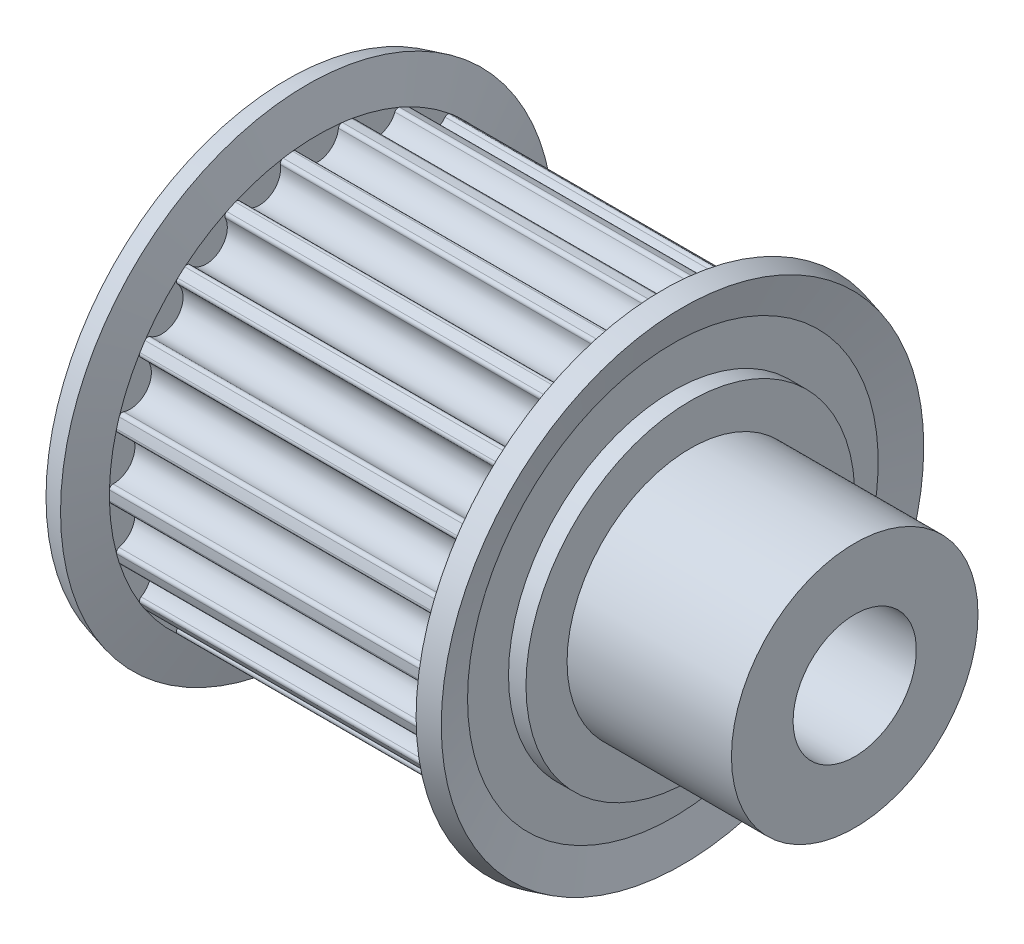
SolidWorks part; units mm, degrees
ref_plane "Front Plane" through (0, 0, 0) normal (0, 0, 1) x (1, 0, 0)
ref_plane "Top Plane" through (0, 0, 0) normal (0, 1, 0) x (1, 0, 0)
ref_plane "Right Plane" through (0, 0, 0) normal (1, 0, 0) x (0, 0, -1)
ref_plane "Plane1" through (0, 0, 0) normal (0, 0, 1) x (1, 0, 0)
sketch "Sketch1" plane through (0, 0, 0) normal (0, 0, 1) x (1, 0, 0)
  line L0 (0, 0) -> (0, 8)
  line L1 (0, 8) -> (0.85, 8)
  line L2 (0.85, 8) -> (0.85, 9.9933)
  line L3 (0.85, 9.9933) -> (0.3817, 11.7412)
  line L4 (0.3817, 11.7412) -> (1.3476, 12)
  line L5 (1.3476, 12) -> (1.85, 10.125)
  line L6 (1.85, 10.125) -> (18.15, 10.125)
  line L7 (18.15, 10.125) -> (18.6524, 12)
  line L8 (18.6524, 12) -> (19.6183, 11.7412)
  line L9 (19.6183, 11.7412) -> (19.15, 9.9933)
  line L10 (19.15, 9.9933) -> (19.15, 8)
  line L11 (19.15, 8) -> (20, 8)
  line L12 (20, 8) -> (20, 6)
  line L13 (20, 6) -> (28, 6)
  line L14 (28, 6) -> (28, 0)
  line L15 (28, 0) -> (0, 0)
  line L16 (28, 0) -> (0, 0) construction
revolve "Revolve1" add sketch "Sketch1" angle 360 about L16
ref_plane "Plane2" through (10, 0, 0) normal (1, 0, 0) x (0, 0, -1)
sketch "Sketch2" plane through (10, 0, 0) normal (1, 0, 0) x (0, 0, -1)
  line L0 (-1.2586, 10.4293) -> (-1.2131, 10.0521)
  line L1 (1.2131, 10.0521) -> (1.2586, 10.4293)
  arc A0 (-1.2131, 10.0521) -> (-1.0238, 9.9019) centre (-1.1927, 9.8833) cw
  arc A1 (-1.0238, 9.9019) -> (1.0238, 9.9019) centre (0, 10.015) ccw
  arc A2 (1.0238, 9.9019) -> (1.2131, 10.0521) centre (1.1927, 9.8833) cw
  arc A3 (1.2586, 10.4293) -> (-1.2586, 10.4293) centre (0, 0) ccw
extrude "Cut-Extrude1" cut sketch "Sketch2" against normal blind 8.15 and the other way blind 8.15
ref_plane "Plane3" through (10, 0, 0) normal (1, 0, 0) x (0, 0, -1)
sketch "Sketch3" plane through (10, 0, 0) normal (1, 0, 0) x (0, 0, -1)
  line L0 (-4.1459, 9.6523) -> (-3.996, 9.3031)
  line L1 (-1.668, 9.9867) -> (-1.7306, 10.3615)
  arc A0 (-3.996, 9.3031) -> (-3.772, 9.2124) centre (-3.9289, 9.1469) cw
  arc A1 (-3.772, 9.2124) -> (-1.8074, 9.7893) centre (-2.8216, 9.6093) ccw
  arc A2 (-1.8074, 9.7893) -> (-1.668, 9.9867) centre (-1.64, 9.819) cw
  arc A3 (-1.7306, 10.3615) -> (-4.1459, 9.6523) centre (0, 0) ccw
extrude "Cut-Extrude2" cut sketch "Sketch3" against normal blind 8.15 and the other way blind 8.15
ref_plane "Plane4" through (10, 0, 0) normal (1, 0, 0) x (0, 0, -1)
sketch "Sketch4" plane through (10, 0, 0) normal (1, 0, 0) x (0, 0, -1)
  line L0 (-6.6974, 8.0932) -> (-6.4551, 7.8005)
  line L1 (-4.414, 9.1122) -> (-4.5797, 9.4542)
  arc A0 (-6.4551, 7.8005) -> (-6.2147, 7.7766) centre (-6.3467, 7.6695) cw
  arc A1 (-6.2147, 7.7766) -> (-4.4921, 8.8835) centre (-5.4145, 8.4252) ccw
  arc A2 (-4.4921, 8.8835) -> (-4.414, 9.1122) centre (-4.3399, 8.9592) cw
  arc A3 (-4.5797, 9.4542) -> (-6.6974, 8.0932) centre (0, 0) ccw
extrude "Cut-Extrude3" cut sketch "Sketch4" against normal blind 8.15 and the other way blind 8.15
ref_plane "Plane5" through (10, 0, 0) normal (1, 0, 0) x (0, 0, -1)
sketch "Sketch5" plane through (10, 0, 0) normal (1, 0, 0) x (0, 0, -1)
  line L0 (-8.7062, 5.8785) -> (-8.3913, 5.6659)
  line L1 (-6.8024, 7.4995) -> (-7.0577, 7.781)
  arc A0 (-8.3913, 5.6659) -> (-8.1538, 5.7107) centre (-8.2504, 5.5708) cw
  arc A1 (-8.1538, 5.7107) -> (-6.813, 7.2581) centre (-7.5688, 6.5584) ccw
  arc A2 (-6.813, 7.2581) -> (-6.8024, 7.4995) centre (-6.6882, 7.3736) cw
  arc A3 (-7.0577, 7.781) -> (-8.7062, 5.8785) centre (0, 0) ccw
extrude "Cut-Extrude4" cut sketch "Sketch5" against normal blind 8.15 and the other way blind 8.15
ref_plane "Plane6" through (10, 0, 0) normal (1, 0, 0) x (0, 0, -1)
sketch "Sketch6" plane through (10, 0, 0) normal (1, 0, 0) x (0, 0, -1)
  line L0 (-10.0097, 3.1876) -> (-9.6476, 3.0723)
  line L1 (-8.6397, 5.2793) -> (-8.964, 5.4774)
  arc A0 (-9.6476, 3.0723) -> (-9.4324, 3.1822) centre (-9.4856, 3.0207) cw
  arc A1 (-9.4324, 3.1822) -> (-8.5818, 5.0447) centre (-9.11, 4.1604) ccw
  arc A2 (-8.5818, 5.0447) -> (-8.6397, 5.2793) centre (-8.4947, 5.1906) cw
  arc A3 (-8.964, 5.4774) -> (-10.0097, 3.1876) centre (0, 0) ccw
extrude "Cut-Extrude5" cut sketch "Sketch6" against normal blind 8.15 and the other way blind 8.15
ref_plane "Plane7" through (10, 0, 0) normal (1, 0, 0) x (0, 0, -1)
sketch "Sketch7" plane through (10, 0, 0) normal (1, 0, 0) x (0, 0, -1)
  line L0 (-10.5023, 0.2384) -> (-10.1224, 0.2298)
  line L1 (-9.7771, 2.6313) -> (-10.144, 2.7301)
  arc A0 (-10.1224, 0.2298) -> (-9.9469, 0.3958) centre (-9.9524, 0.2259) cw
  arc A1 (-9.9469, 0.3958) -> (-9.6555, 2.4226) centre (-9.9131, 1.4253) ccw
  arc A2 (-9.6555, 2.4226) -> (-9.7771, 2.6313) centre (-9.6129, 2.5871) cw
  arc A3 (-10.144, 2.7301) -> (-10.5023, 0.2384) centre (0, 0) ccw
extrude "Cut-Extrude6" cut sketch "Sketch7" against normal blind 8.15 and the other way blind 8.15
ref_plane "Plane8" through (10, 0, 0) normal (1, 0, 0) x (0, 0, -1)
sketch "Sketch8" plane through (10, 0, 0) normal (1, 0, 0) x (0, 0, -1)
  line L0 (-10.144, -2.7301) -> (-9.7771, -2.6313)
  line L1 (-10.1224, -0.2298) -> (-10.5023, -0.2384)
  arc A0 (-9.7771, -2.6313) -> (-9.6555, -2.4226) centre (-9.6129, -2.5871) cw
  arc A1 (-9.6555, -2.4226) -> (-9.9469, -0.3958) centre (-9.9131, -1.4253) ccw
  arc A2 (-9.9469, -0.3958) -> (-10.1224, -0.2298) centre (-9.9524, -0.2259) cw
  arc A3 (-10.5023, -0.2384) -> (-10.144, -2.7301) centre (0, 0) ccw
extrude "Cut-Extrude7" cut sketch "Sketch8" against normal blind 8.15 and the other way blind 8.15
ref_plane "Plane9" through (10, 0, 0) normal (1, 0, 0) x (0, 0, -1)
sketch "Sketch9" plane through (10, 0, 0) normal (1, 0, 0) x (0, 0, -1)
  line L0 (-8.964, -5.4774) -> (-8.6397, -5.2793)
  line L1 (-9.6476, -3.0723) -> (-10.0097, -3.1876)
  arc A0 (-8.6397, -5.2793) -> (-8.5818, -5.0447) centre (-8.4947, -5.1906) cw
  arc A1 (-8.5818, -5.0447) -> (-9.4324, -3.1822) centre (-9.11, -4.1604) ccw
  arc A2 (-9.4324, -3.1822) -> (-9.6476, -3.0723) centre (-9.4856, -3.0207) cw
  arc A3 (-10.0097, -3.1876) -> (-8.964, -5.4774) centre (0, 0) ccw
extrude "Cut-Extrude8" cut sketch "Sketch9" against normal blind 8.15 and the other way blind 8.15
ref_plane "Plane10" through (10, 0, 0) normal (1, 0, 0) x (0, 0, -1)
sketch "Sketch10" plane through (10, 0, 0) normal (1, 0, 0) x (0, 0, -1)
  line L0 (-7.0577, -7.781) -> (-6.8024, -7.4995)
  line L1 (-8.3913, -5.6659) -> (-8.7062, -5.8785)
  arc A0 (-6.8024, -7.4995) -> (-6.813, -7.2581) centre (-6.6882, -7.3736) cw
  arc A1 (-6.813, -7.2581) -> (-8.1538, -5.7107) centre (-7.5688, -6.5584) ccw
  arc A2 (-8.1538, -5.7107) -> (-8.3913, -5.6659) centre (-8.2504, -5.5708) cw
  arc A3 (-8.7062, -5.8785) -> (-7.0577, -7.781) centre (0, 0) ccw
extrude "Cut-Extrude9" cut sketch "Sketch10" against normal blind 8.15 and the other way blind 8.15
ref_plane "Plane11" through (10, 0, 0) normal (1, 0, 0) x (0, 0, -1)
sketch "Sketch11" plane through (10, 0, 0) normal (1, 0, 0) x (0, 0, -1)
  line L0 (-4.5797, -9.4542) -> (-4.414, -9.1122)
  line L1 (-6.4551, -7.8005) -> (-6.6974, -8.0932)
  arc A0 (-4.414, -9.1122) -> (-4.4921, -8.8835) centre (-4.3399, -8.9592) cw
  arc A1 (-4.4921, -8.8835) -> (-6.2147, -7.7766) centre (-5.4145, -8.4252) ccw
  arc A2 (-6.2147, -7.7766) -> (-6.4551, -7.8005) centre (-6.3467, -7.6695) cw
  arc A3 (-6.6974, -8.0932) -> (-4.5797, -9.4542) centre (0, 0) ccw
extrude "Cut-Extrude10" cut sketch "Sketch11" against normal blind 8.15 and the other way blind 8.15
ref_plane "Plane12" through (10, 0, 0) normal (1, 0, 0) x (0, 0, -1)
sketch "Sketch12" plane through (10, 0, 0) normal (1, 0, 0) x (0, 0, -1)
  line L0 (-1.7306, -10.3615) -> (-1.668, -9.9867)
  line L1 (-3.996, -9.3031) -> (-4.1459, -9.6523)
  arc A0 (-1.668, -9.9867) -> (-1.8074, -9.7893) centre (-1.64, -9.819) cw
  arc A1 (-1.8074, -9.7893) -> (-3.772, -9.2124) centre (-2.8216, -9.6093) ccw
  arc A2 (-3.772, -9.2124) -> (-3.996, -9.3031) centre (-3.9289, -9.1469) cw
  arc A3 (-4.1459, -9.6523) -> (-1.7306, -10.3615) centre (0, 0) ccw
extrude "Cut-Extrude11" cut sketch "Sketch12" against normal blind 8.15 and the other way blind 8.15
ref_plane "Plane13" through (10, 0, 0) normal (1, 0, 0) x (0, 0, -1)
sketch "Sketch13" plane through (10, 0, 0) normal (1, 0, 0) x (0, 0, -1)
  line L0 (1.2586, -10.4293) -> (1.2131, -10.0521)
  line L1 (-1.2131, -10.0521) -> (-1.2586, -10.4293)
  arc A0 (1.2131, -10.0521) -> (1.0238, -9.9019) centre (1.1927, -9.8833) cw
  arc A1 (1.0238, -9.9019) -> (-1.0238, -9.9019) centre (0, -10.015) ccw
  arc A2 (-1.0238, -9.9019) -> (-1.2131, -10.0521) centre (-1.1927, -9.8833) cw
  arc A3 (-1.2586, -10.4293) -> (1.2586, -10.4293) centre (0, 0) ccw
extrude "Cut-Extrude12" cut sketch "Sketch13" against normal blind 8.15 and the other way blind 8.15
ref_plane "Plane14" through (10, 0, 0) normal (1, 0, 0) x (0, 0, -1)
sketch "Sketch14" plane through (10, 0, 0) normal (1, 0, 0) x (0, 0, -1)
  line L0 (4.1459, -9.6523) -> (3.996, -9.3031)
  line L1 (1.668, -9.9867) -> (1.7306, -10.3615)
  arc A0 (3.996, -9.3031) -> (3.772, -9.2124) centre (3.9289, -9.1469) cw
  arc A1 (3.772, -9.2124) -> (1.8074, -9.7893) centre (2.8216, -9.6093) ccw
  arc A2 (1.8074, -9.7893) -> (1.668, -9.9867) centre (1.64, -9.819) cw
  arc A3 (1.7306, -10.3615) -> (4.1459, -9.6523) centre (0, 0) ccw
extrude "Cut-Extrude13" cut sketch "Sketch14" against normal blind 8.15 and the other way blind 8.15
ref_plane "Plane15" through (10, 0, 0) normal (1, 0, 0) x (0, 0, -1)
sketch "Sketch15" plane through (10, 0, 0) normal (1, 0, 0) x (0, 0, -1)
  line L0 (6.6974, -8.0932) -> (6.4551, -7.8005)
  line L1 (4.414, -9.1122) -> (4.5797, -9.4542)
  arc A0 (6.4551, -7.8005) -> (6.2147, -7.7766) centre (6.3467, -7.6695) cw
  arc A1 (6.2147, -7.7766) -> (4.4921, -8.8835) centre (5.4145, -8.4252) ccw
  arc A2 (4.4921, -8.8835) -> (4.414, -9.1122) centre (4.3399, -8.9592) cw
  arc A3 (4.5797, -9.4542) -> (6.6974, -8.0932) centre (0, 0) ccw
extrude "Cut-Extrude14" cut sketch "Sketch15" against normal blind 8.15 and the other way blind 8.15
ref_plane "Plane16" through (10, 0, 0) normal (1, 0, 0) x (0, 0, -1)
sketch "Sketch16" plane through (10, 0, 0) normal (1, 0, 0) x (0, 0, -1)
  line L0 (8.7062, -5.8785) -> (8.3913, -5.6659)
  line L1 (6.8024, -7.4995) -> (7.0577, -7.781)
  arc A0 (8.3913, -5.6659) -> (8.1538, -5.7107) centre (8.2504, -5.5708) cw
  arc A1 (8.1538, -5.7107) -> (6.813, -7.2581) centre (7.5688, -6.5584) ccw
  arc A2 (6.813, -7.2581) -> (6.8024, -7.4995) centre (6.6882, -7.3736) cw
  arc A3 (7.0577, -7.781) -> (8.7062, -5.8785) centre (0, 0) ccw
extrude "Cut-Extrude15" cut sketch "Sketch16" against normal blind 8.15 and the other way blind 8.15
ref_plane "Plane17" through (10, 0, 0) normal (1, 0, 0) x (0, 0, -1)
sketch "Sketch17" plane through (10, 0, 0) normal (1, 0, 0) x (0, 0, -1)
  line L0 (10.0097, -3.1876) -> (9.6476, -3.0723)
  line L1 (8.6397, -5.2793) -> (8.964, -5.4774)
  arc A0 (9.6476, -3.0723) -> (9.4324, -3.1822) centre (9.4856, -3.0207) cw
  arc A1 (9.4324, -3.1822) -> (8.5818, -5.0447) centre (9.11, -4.1604) ccw
  arc A2 (8.5818, -5.0447) -> (8.6397, -5.2793) centre (8.4947, -5.1906) cw
  arc A3 (8.964, -5.4774) -> (10.0097, -3.1876) centre (0, 0) ccw
extrude "Cut-Extrude16" cut sketch "Sketch17" against normal blind 8.15 and the other way blind 8.15
ref_plane "Plane18" through (10, 0, 0) normal (1, 0, 0) x (0, 0, -1)
sketch "Sketch18" plane through (10, 0, 0) normal (1, 0, 0) x (0, 0, -1)
  line L0 (10.5023, -0.2384) -> (10.1224, -0.2298)
  line L1 (9.7771, -2.6313) -> (10.144, -2.7301)
  arc A0 (10.1224, -0.2298) -> (9.9469, -0.3958) centre (9.9524, -0.2259) cw
  arc A1 (9.9469, -0.3958) -> (9.6555, -2.4226) centre (9.9131, -1.4253) ccw
  arc A2 (9.6555, -2.4226) -> (9.7771, -2.6313) centre (9.6129, -2.5871) cw
  arc A3 (10.144, -2.7301) -> (10.5023, -0.2384) centre (0, 0) ccw
extrude "Cut-Extrude17" cut sketch "Sketch18" against normal blind 8.15 and the other way blind 8.15
ref_plane "Plane19" through (10, 0, 0) normal (1, 0, 0) x (0, 0, -1)
sketch "Sketch19" plane through (10, 0, 0) normal (1, 0, 0) x (0, 0, -1)
  line L0 (10.144, 2.7301) -> (9.7771, 2.6313)
  line L1 (10.1224, 0.2298) -> (10.5023, 0.2384)
  arc A0 (9.7771, 2.6313) -> (9.6555, 2.4226) centre (9.6129, 2.5871) cw
  arc A1 (9.6555, 2.4226) -> (9.9469, 0.3958) centre (9.9131, 1.4253) ccw
  arc A2 (9.9469, 0.3958) -> (10.1224, 0.2298) centre (9.9524, 0.2259) cw
  arc A3 (10.5023, 0.2384) -> (10.144, 2.7301) centre (0, 0) ccw
extrude "Cut-Extrude18" cut sketch "Sketch19" against normal blind 8.15 and the other way blind 8.15
ref_plane "Plane20" through (10, 0, 0) normal (1, 0, 0) x (0, 0, -1)
sketch "Sketch20" plane through (10, 0, 0) normal (1, 0, 0) x (0, 0, -1)
  line L0 (8.964, 5.4774) -> (8.6397, 5.2793)
  line L1 (9.6476, 3.0723) -> (10.0097, 3.1876)
  arc A0 (8.6397, 5.2793) -> (8.5818, 5.0447) centre (8.4947, 5.1906) cw
  arc A1 (8.5818, 5.0447) -> (9.4324, 3.1822) centre (9.11, 4.1604) ccw
  arc A2 (9.4324, 3.1822) -> (9.6476, 3.0723) centre (9.4856, 3.0207) cw
  arc A3 (10.0097, 3.1876) -> (8.964, 5.4774) centre (0, 0) ccw
extrude "Cut-Extrude19" cut sketch "Sketch20" against normal blind 8.15 and the other way blind 8.15
ref_plane "Plane21" through (10, 0, 0) normal (1, 0, 0) x (0, 0, -1)
sketch "Sketch21" plane through (10, 0, 0) normal (1, 0, 0) x (0, 0, -1)
  line L0 (7.0577, 7.781) -> (6.8024, 7.4995)
  line L1 (8.3913, 5.6659) -> (8.7062, 5.8785)
  arc A0 (6.8024, 7.4995) -> (6.813, 7.2581) centre (6.6882, 7.3736) cw
  arc A1 (6.813, 7.2581) -> (8.1538, 5.7107) centre (7.5688, 6.5584) ccw
  arc A2 (8.1538, 5.7107) -> (8.3913, 5.6659) centre (8.2504, 5.5708) cw
  arc A3 (8.7062, 5.8785) -> (7.0577, 7.781) centre (0, 0) ccw
extrude "Cut-Extrude20" cut sketch "Sketch21" against normal blind 8.15 and the other way blind 8.15
ref_plane "Plane22" through (10, 0, 0) normal (1, 0, 0) x (0, 0, -1)
sketch "Sketch22" plane through (10, 0, 0) normal (1, 0, 0) x (0, 0, -1)
  line L0 (4.5797, 9.4542) -> (4.414, 9.1122)
  line L1 (6.4551, 7.8005) -> (6.6974, 8.0932)
  arc A0 (4.414, 9.1122) -> (4.4921, 8.8835) centre (4.3399, 8.9592) cw
  arc A1 (4.4921, 8.8835) -> (6.2147, 7.7766) centre (5.4145, 8.4252) ccw
  arc A2 (6.2147, 7.7766) -> (6.4551, 7.8005) centre (6.3467, 7.6695) cw
  arc A3 (6.6974, 8.0932) -> (4.5797, 9.4542) centre (0, 0) ccw
extrude "Cut-Extrude21" cut sketch "Sketch22" against normal blind 8.15 and the other way blind 8.15
ref_plane "Plane23" through (10, 0, 0) normal (1, 0, 0) x (0, 0, -1)
sketch "Sketch23" plane through (10, 0, 0) normal (1, 0, 0) x (0, 0, -1)
  line L0 (1.7306, 10.3615) -> (1.668, 9.9867)
  line L1 (3.996, 9.3031) -> (4.1459, 9.6523)
  arc A0 (1.668, 9.9867) -> (1.8074, 9.7893) centre (1.64, 9.819) cw
  arc A1 (1.8074, 9.7893) -> (3.772, 9.2124) centre (2.8216, 9.6093) ccw
  arc A2 (3.772, 9.2124) -> (3.996, 9.3031) centre (3.9289, 9.1469) cw
  arc A3 (4.1459, 9.6523) -> (1.7306, 10.3615) centre (0, 0) ccw
extrude "Cut-Extrude22" cut sketch "Sketch23" against normal blind 8.15 and the other way blind 8.15
ref_plane "Plane24" through (0, 0, 0) normal (0, 0, 1) x (1, 0, 0)
sketch "Sketch24" plane through (0, 0, 0) normal (0, 0, 1) x (1, 0, 0)
  line L0 (0, 0) -> (0, 3)
  line L1 (0, 3) -> (28, 3)
  line L2 (28, 3) -> (28, 0)
  line L3 (28, 0) -> (0, 0)
  line L4 (28, 0) -> (0, 0) construction
revolve "Cut-Revolve1" cut sketch "Sketch24" angle 360 about L4
